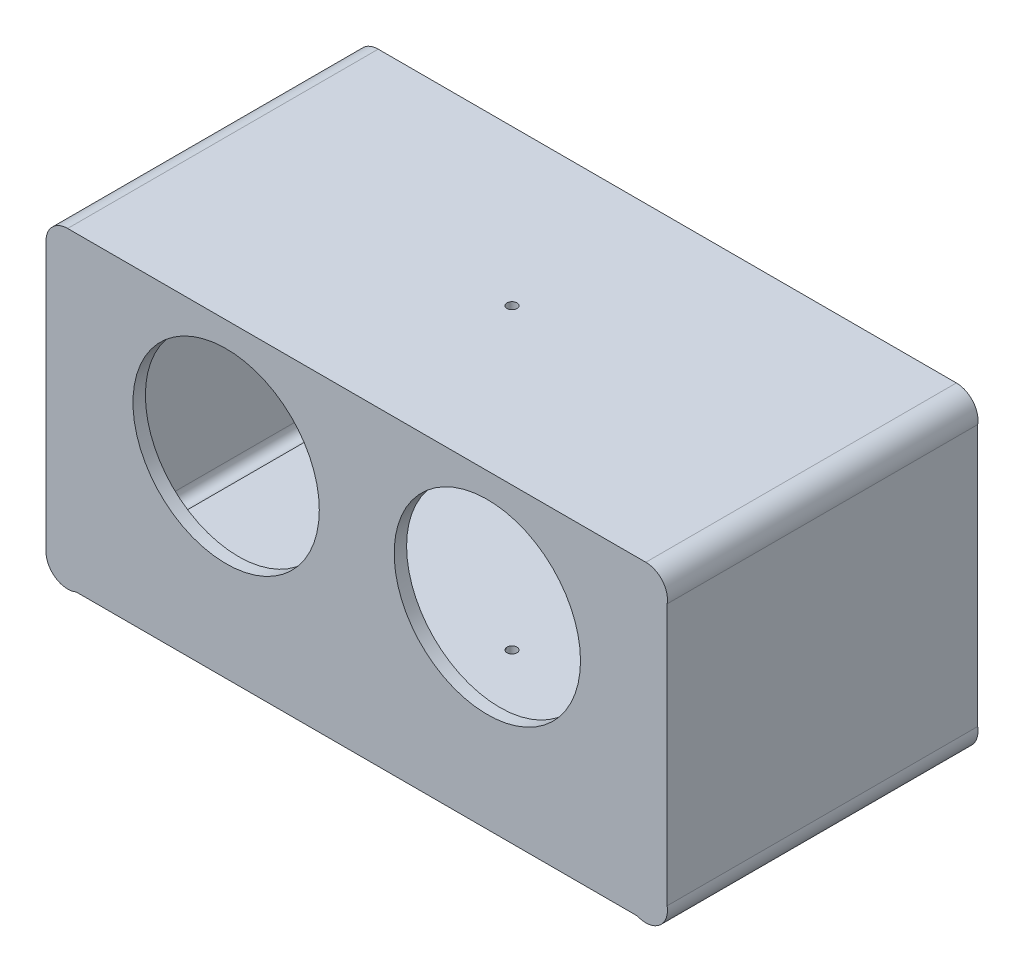
SolidWorks part; units mm, degrees
ref_plane "Front Plane" through (0, 0, 0) normal (0, 0, 1) x (1, 0, 0)
ref_plane "Top Plane" through (0, 0, 0) normal (0, 1, 0) x (1, 0, 0)
ref_plane "Right Plane" through (0, 0, 0) normal (1, 0, 0) x (0, 0, -1)
sketch "Sketch1" plane through (0, 0, 0) normal (0, 0, 1) x (1, 0, 0)
  line L0 (2.4143, 0.07) -> (47.5857, 0.07)
  line L1 (49.9868, 1.9758) -> (49.9868, 23.0242)
  line L2 (-0.0132, 1.6731) -> (-0.0132, 23.3269)
  line L3 (1.7299, 25.07) -> (48.2701, 25.07)
  line L4 (-0.0132, 12.5) -> (49.9868, 12.5) construction
  line L5 (25, 25.07) -> (25, 0.07) construction
  line L6 (6.9868, 15.57) -> (21.9868, 15.57) construction
  line L7 (14.4868, 23.07) -> (14.4868, 25.07) construction
  line L8 (6.9868, 15.57) -> (-0.0132, 15.57) construction
  circle A0 centre (14.4868, 15.57) radius 7.5
  arc A1 (1.7299, 25.07) -> (-0.0132, 23.3269) centre (1.7299, 23.3269) ccw
  circle A2 centre (35.5132, 15.57) radius 7.5
  arc A3 (48.2701, 25.07) -> (49.9868, 23.0242) centre (48.2701, 23.3269) cw
  arc A4 (47.5857, 0.07) -> (49.9868, 1.9758) centre (48.2701, 1.6731) ccw
  arc A5 (2.4143, 0.07) -> (-0.0132, 1.6731) centre (1.7299, 1.6731) cw
  circle A6 centre (14.4868, 15.57) radius 6.5
  circle A7 centre (35.5132, 15.57) radius 6.5
  point P2 (0, 0)
  point P30 (0, 0)
  point P31 (0, 0)
  point P32 (0, 0)
  dimension "D4" = 2
  dimension "D1" = 1
  dimension "D2" = 1
  dimension "D3" = 15
  dimension "D5" = 7
extrude "Boss-Extrude2" add sketch "Sketch1" against normal blind 25 contours A5 L0 A4 L1 A3 L3 A1 L2 A0 A2
sketch "Sketch2" plane through (0, 0, -25) normal (0, 0, -1) x (-1, 0, 0)
  line L8 (-0.9868, 1.6731) -> (-0.9868, 23.3269)
  line L9 (-1.7299, 24.07) -> (-48.2701, 24.07)
  line L10 (-48.9868, 23.1303) -> (-48.9868, 1.8697)
  line L11 (-47.836, 1.07) -> (-2.164, 1.07)
  line L12 (-0.9868, 1.6731) -> (-0.9868, 23.3269)
  line L13 (-1.7299, 24.07) -> (-48.2701, 24.07)
  line L14 (-48.9868, 23.1303) -> (-48.9868, 1.8697)
  line L15 (-47.836, 1.07) -> (-2.164, 1.07)
  arc A8 (-2.164, 1.07) -> (-0.9868, 1.6731) centre (-1.7299, 1.6731) ccw
  arc A9 (-0.9868, 23.3269) -> (-1.7299, 24.07) centre (-1.7299, 23.3269) ccw
  arc A10 (-48.2701, 24.07) -> (-48.9868, 23.1303) centre (-48.2701, 23.3269) ccw
  arc A11 (-48.9868, 1.8697) -> (-47.836, 1.07) centre (-48.2701, 1.6731) ccw
  arc A12 (-2.164, 1.07) -> (-0.9868, 1.6731) centre (-1.7299, 1.6731) ccw
  arc A13 (-0.9868, 23.3269) -> (-1.7299, 24.07) centre (-1.7299, 23.3269) ccw
  arc A14 (-48.2701, 24.07) -> (-48.9868, 23.1303) centre (-48.2701, 23.3269) ccw
  arc A15 (-48.9868, 1.8697) -> (-47.836, 1.07) centre (-48.2701, 1.6731) ccw
  dimension "D1" = 1
extrude "Cut-Extrude1" cut sketch "Sketch2" against normal blind 24
sketch "Sketch3" plane through (0, 0.07, 0) normal (0, -1, 0) x (1, 0, 0)
  line L0 (2.4143, 0) -> (47.5857, -25) construction
  circle A0 centre (25, -12.5) radius 0.4
extrude "Cut-Extrude2" cut sketch "Sketch3" against normal blind 36 and the other way blind 27
sketch "Sketch4" plane through (0, 0.07, 0) normal (0, -1, 0) x (1, 0, 0)
  circle A0 centre (25, -12.5) radius 7
extrude "Boss-Extrude3" add sketch "Sketch4" along normal blind 1
sketch "Sketch5" plane through (0, 1.07, 0) normal (0, 1, 0) x (1, 0, 0)
  circle A0 centre (25, 12.5) radius 0.4
extrude "Cut-Extrude3" cut sketch "Sketch5" against normal blind 11
